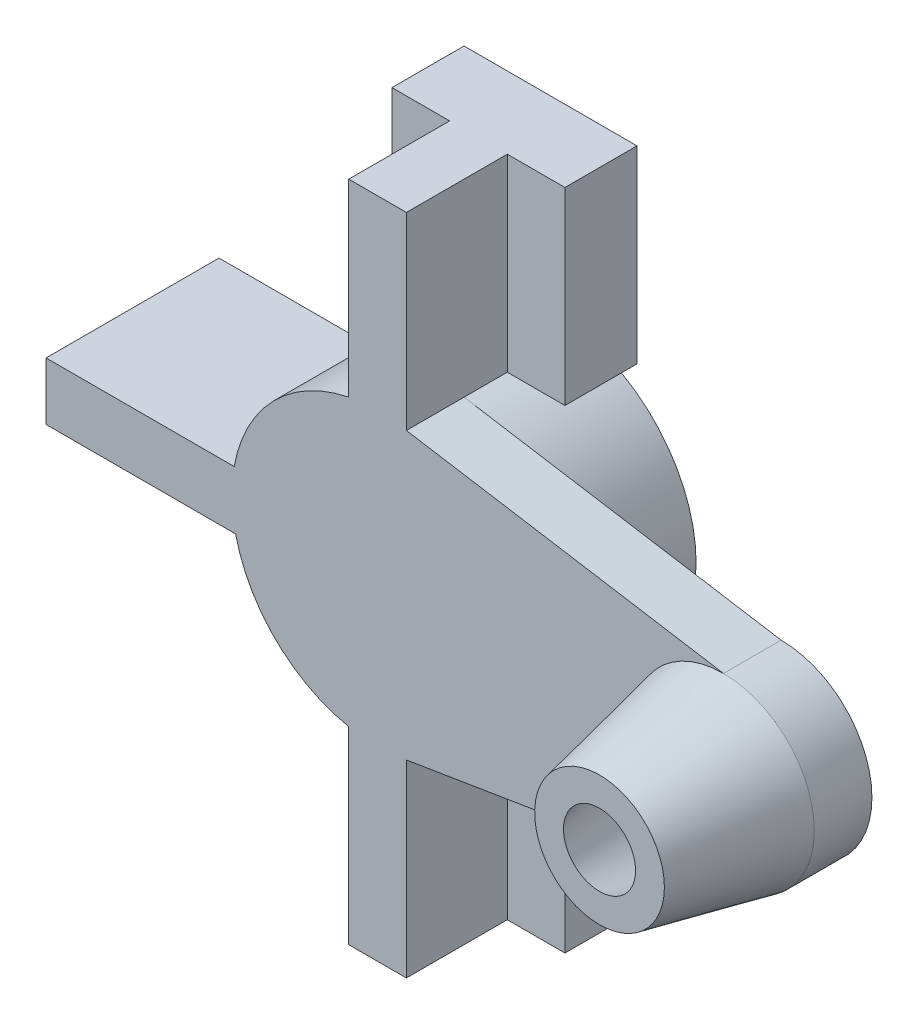
SolidWorks part; units mm, degrees
ref_plane "Plano frontal" through (0, 0, 0) normal (0, 0, 1) x (1, 0, 0)
ref_plane "Plano superior" through (0, 0, 0) normal (0, 1, 0) x (1, 0, 0)
ref_plane "Plano direito" through (0, 0, 0) normal (1, 0, 0) x (0, 0, -1)
sketch "Esboço2" plane through (0, 0, 0) normal (0, 0, 1) x (1, 0, 0)
  line L0 (-10, 115) -> (-10, 49.5)
  line L1 (-10, 115) -> (10, 115)
  line L2 (10, 115) -> (10, 49.5)
  line L3 (-115, 8.7895) -> (-49.7292, 8.7895)
  line L4 (-115, 8.7895) -> (-115, -11.2105)
  line L5 (-115, -11.2105) -> (-49.24, -11.2105)
  line L6 (-131.9028, 0) -> (190.6667, 0) construction
  line L7 (10, -115) -> (10, -49.5)
  line L8 (-10, -115) -> (-10, -49.5)
  line L9 (-10, -115) -> (10, -115)
  line L10 (0, 108.4366) -> (0, -107.1442) construction
  line L11 (120, 31.5) -> (10, 49.5)
  line L12 (120, -31.5) -> (10, -49.5)
  arc A1 (120, -31.5) -> (120, 31.5) centre (120, 0) ccw
  arc A6 (-10, 49.5) -> (-49.7292, 8.7895) centre (0, 0) ccw
  arc A7 (-49.24, -11.2105) -> (-10, -49.5) centre (0, 0) ccw
  dimension "D3" = 63
  dimension "D6" = 101
  dimension "D7" = 120
  dimension "D8" = 20
  dimension "D9" = 20
  dimension "D10" = 10
  dimension "D11" = 230
  dimension "D12" = 115
extrude "Ressalto-extrusão4" add sketch "Esboço2" along normal blind 20
sketch "Esboço3" plane through (0, 0, 0) normal (0, 1, 0) x (1, 0, 0)
  line L0 (120, -63) -> (120, -20)
  line L1 (10, -20) -> (120, -20) construction
  line L2 (120, -20) -> (151.5, -20)
  line L3 (120, -20) -> (151.5, -20) construction
  line L4 (151.5, -20) -> (142.5, -63)
  line L5 (142.5, -63) -> (120, -63)
  dimension "D1" = 31.5
  dimension "D2" = 22.5
  dimension "D3" = 43
revolve "Revolução2" add sketch "Esboço3" angle 360 about L0
sketch "Esboço5" plane through (0, 0, 0) normal (0, 1, 0) x (1, 0, 0)
  line L0 (120, -20) -> (120, -63)
  line L1 (97.5, -63) -> (142.5, -63) construction
  line L2 (120, -63) -> (132.5, -63)
  line L3 (132.5, -63) -> (142.5, -20)
  line L4 (142.5, -20) -> (120, -20)
  dimension "D1" = 12.5
revolve "Corte-Revolução1" cut sketch "Esboço5" angle 360 about L0
sketch "Esboço6" plane through (0, 0, 0) normal (0, 0, -1) x (-1, 0, 0)
  circle A0 centre (0, 0) radius 50.5
extrude "Ressalto-extrusão5" add sketch "Esboço6" along normal blind 40
sketch "Esboço7" plane through (0, 0, 0) normal (0, 0, -1) x (-1, 0, 0)
  line L3 (-10, -49.5) -> (-10, -115)
  line L4 (-10, -115) -> (10, -115)
  line L5 (10, -115) -> (10, -49.5)
  line L6 (-10, -49.5) -> (-10, -115)
  line L7 (-10, -115) -> (10, -115)
  line L8 (10, -115) -> (10, -49.5)
  arc A1 (-10, -49.5) -> (10, -49.5) centre (0, 0) ccw
  arc A2 (-10, -49.5) -> (10, -49.5) centre (0, 0) ccw
  dimension "D1" = 0
extrude "Ressalto-extrusão6" add sketch "Esboço7" along normal blind 40 contours L8 A2 L6 L7
sketch "Esboço8" plane through (0, 0, 0) normal (0, 0, -1) x (-1, 0, 0)
  line L3 (10, 49.5) -> (10, 115)
  line L4 (10, 115) -> (-10, 115)
  line L5 (-10, 115) -> (-10, 49.5)
  line L6 (10, 49.5) -> (10, 115)
  line L7 (10, 115) -> (-10, 115)
  line L8 (-10, 115) -> (-10, 49.5)
  arc A1 (10, 49.5) -> (-10, 49.5) centre (0, 0) ccw
  arc A2 (10, 49.5) -> (-10, 49.5) centre (0, 0) ccw
  dimension "D1" = 0
extrude "Ressalto-extrusão7" add sketch "Esboço8" along normal blind 40
ref_plane "Plano1" through (-49.7292, 8.7895, 0) normal (-1, 0, 0) x (0, 0, 1)
sketch "Esboço10" plane through (0, 0, 0) normal (0, 0, -1) x (-1, 0, 0)
  line L3 (49.24, -11.2105) -> (115, -11.2105)
  line L4 (115, -11.2105) -> (115, 8.7895)
  line L5 (115, 8.7895) -> (49.7292, 8.7895)
  line L6 (49.24, -11.2105) -> (115, -11.2105)
  line L7 (115, -11.2105) -> (115, 8.7895)
  line L8 (115, 8.7895) -> (49.7292, 8.7895)
  arc A1 (49.24, -11.2105) -> (49.7292, 8.7895) centre (0, 0) ccw
  arc A2 (49.24, -11.2105) -> (49.7292, 8.7895) centre (0, 0) ccw
  dimension "D1" = 0
extrude "Ressalto-extrusão8" add sketch "Esboço10" along normal blind 40
ref_plane "Plano3" through (0, 0, -40) normal (0, 0, -1) x (-1, 0, 0)
sketch "Esboço12" plane through (0, 0, -40) normal (0, 0, -1) x (-1, 0, 0)
  line L0 (123.2092, 0) -> (-165.4967, 0) construction
  line L1 (10, 115) -> (-10, 115) construction
  line L2 (-30, 49.5) -> (30, 49.5)
  line L3 (-30, 49.5) -> (-30, 115)
  line L4 (-30, 115) -> (30, 115)
  line L5 (30, 49.5) -> (30, 115)
  line L6 (-30, 49.5) -> (30, 115) construction
  line L7 (-30, 115) -> (30, 49.5) construction
  line L8 (-30, -115) -> (30, -49.5) construction
  line L9 (-30, -49.5) -> (30, -115) construction
  line L10 (30, -49.5) -> (30, -115)
  line L11 (-30, -115) -> (30, -115)
  line L12 (-30, -49.5) -> (-30, -115)
  line L13 (-30, -49.5) -> (30, -49.5)
  point P3 (0, 82.25)
  point P16 (0, -82.25)
  dimension "D1" = 60
  dimension "D2" = 20
extrude "Ressalto-extrusão9" add sketch "Esboço12" against normal blind 25
